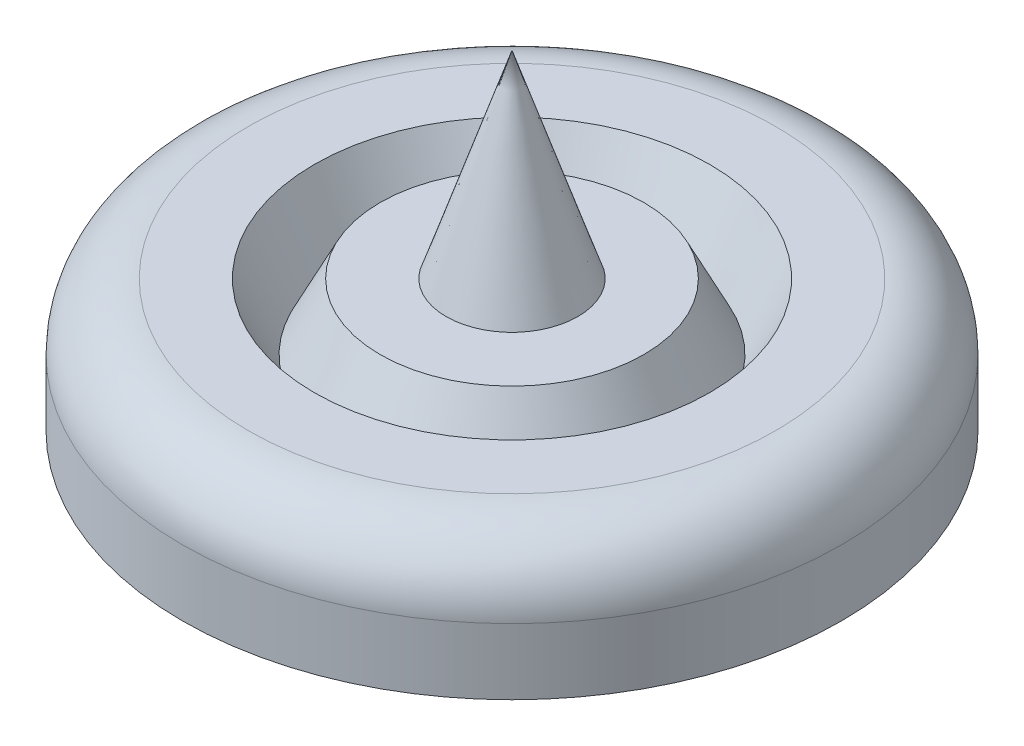
SolidWorks part; units mm, degrees
ref_plane "Front Plane" through (0, 0, 0) normal (0, 0, 1) x (1, 0, 0)
ref_plane "Top Plane" through (0, 0, 0) normal (0, 1, 0) x (1, 0, 0)
ref_plane "Right Plane" through (0, 0, 0) normal (1, 0, 0) x (0, 0, -1)
sketch "Sketch6" plane through (0, 0, 0) normal (0, 0, 1) x (1, 0, 0)
  line L1 (0, 25.4) -> (25.4, 0)
  line L4 (25.4, 50.8) -> (50.8, 50.8)
  line L5 (127, 25.4) -> (127, 0)
  line L8 (0, 127) -> (25.4, 50.8)
  line L9 (50.8, 50.8) -> (63.5, 25.4)
  line L10 (63.5, 25.4) -> (76.2, 50.8)
  line L11 (25.4, 0) -> (127, 0)
  line L13 (76.2, 50.8) -> (101.6, 50.8)
  line L14 (0, 127) -> (0, 25.4)
  arc A0 (127, 25.4) -> (101.6, 50.8) centre (101.6, 25.4) ccw
  point P15 (127, 50.8)
  dimension "D1" = 25.4
  dimension "D2" = 101.6
  dimension "D3" = 101.6
  dimension "D4" = 50.8
  dimension "D5" = 25.4
  dimension "D6" = 25.4
  dimension "D7" = 50.8
  dimension "D8" = 0
  dimension "D9" = 76.2
revolve "Revolve1" add sketch "Sketch6" angle 360 about L14
